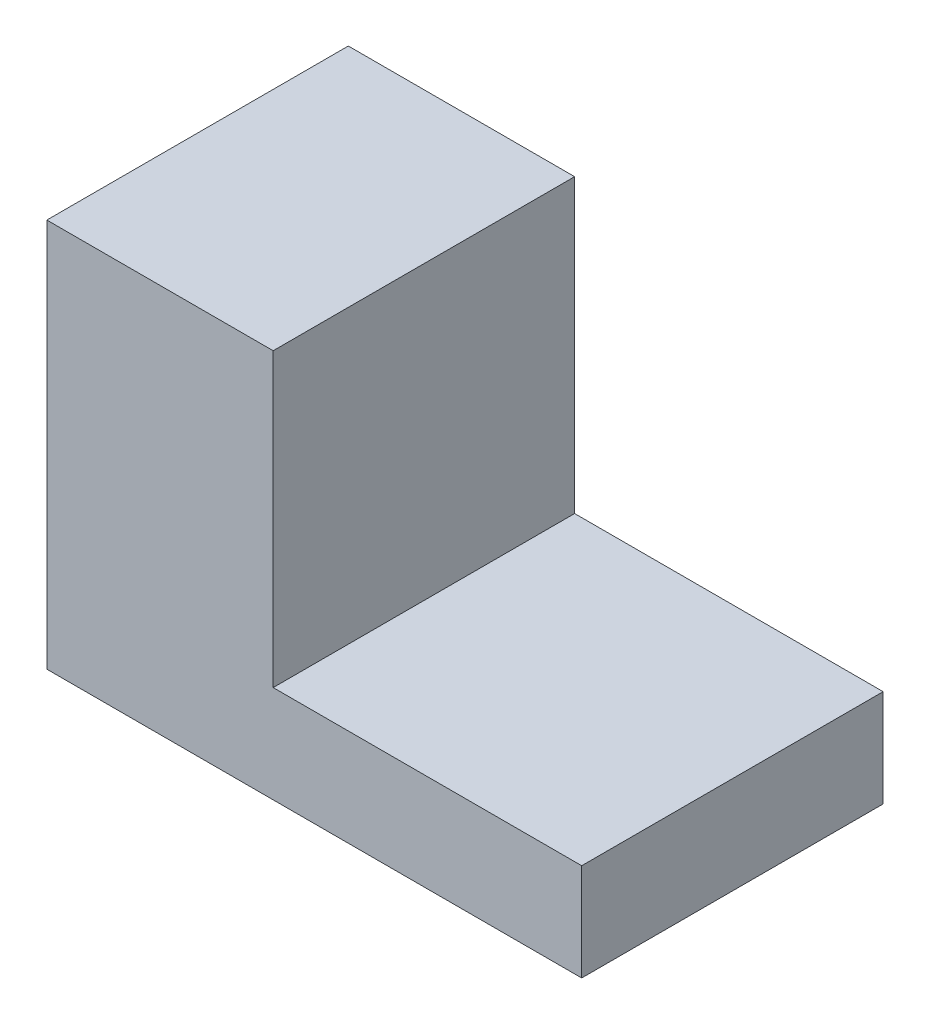
SolidWorks part; units mm, degrees
ref_plane "Спереди" through (0, 0, 0) normal (0, 0, 1) x (1, 0, 0)
ref_plane "Сверху" through (0, 0, 0) normal (0, 1, 0) x (1, 0, 0)
ref_plane "Справа" through (0, 0, 0) normal (1, 0, 0) x (0, 0, -1)
other "Configuration Table"
sketch "Эскиз1" plane through (0, 0, 0) normal (0, 1, 0) x (1, 0, 0)
  line L1 (0, 0) -> (1100, 0)
  line L2 (0, 0) -> (0, 620)
  line L3 (0, 620) -> (1100, 620)
  line L4 (1100, 0) -> (1100, 620)
  dimension "D1" = 620
  dimension "D2" = 1100
extrude "Бобышка-Вытянуть1" add sketch "Эскиз1" along normal blind 800 contours L2 L1 L4 L3
sketch "Эскиз2" plane through (0, 800, 0) normal (0, 1, 0) x (1, 0, 0)
  line L0 (0, 0) -> (1100, 0) construction
  line L1 (1100, 620) -> (465.4597, 620)
  line L2 (1100, 620) -> (1100, 0)
  line L3 (1100, 0) -> (465.4597, 0)
  line L4 (465.4597, 620) -> (465.4597, 0)
extrude "Вырез-Вытянуть1" cut sketch "Эскиз2" against normal blind 600
